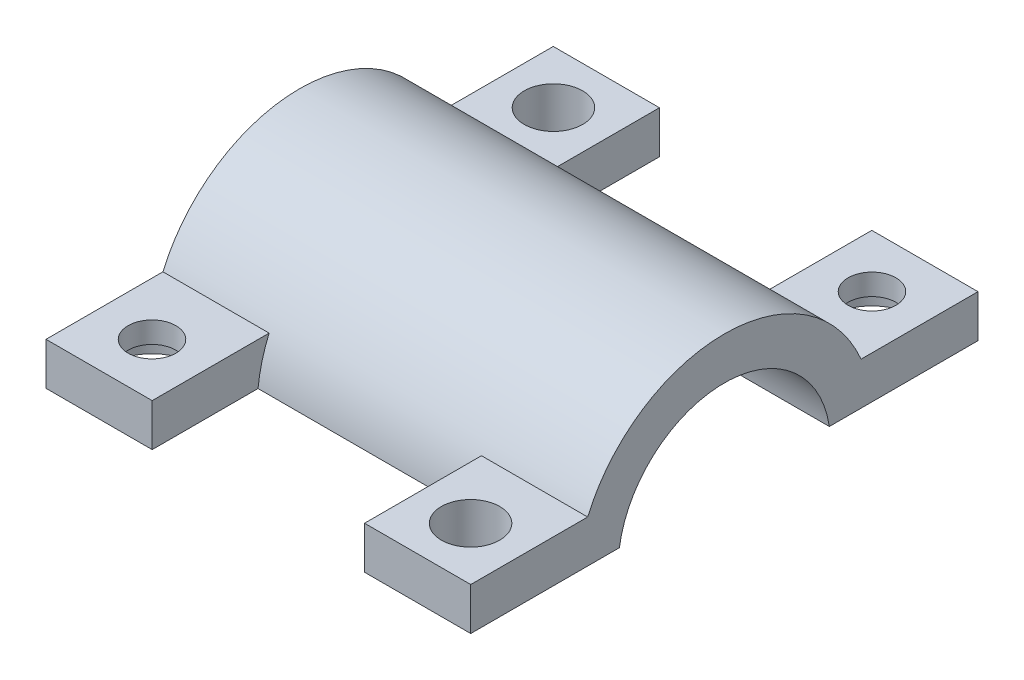
SolidWorks part; units mm, degrees
ref_plane "Front Plane" through (0, 0, 0) normal (0, 0, 1) x (1, 0, 0)
ref_plane "Top Plane" through (0, 0, 0) normal (0, 1, 0) x (1, 0, 0)
ref_plane "Right Plane" through (0, 0, 0) normal (1, 0, 0) x (0, 0, -1)
sketch "Sketch1" plane through (0, 0, 0) normal (1, 0, 0) x (0, 0, -1)
  line L0 (-49.4052, 0) -> (68.181, 0) construction
  line L1 (-13.9194, 1.5) -> (-9.8869, 1.5)
  line L2 (9.8869, 1.5) -> (13.9194, 1.5)
  arc A2 (9.8869, 1.5) -> (-9.8869, 1.5) centre (0, 0) ccw
  arc A3 (-13.9194, 1.5) -> (13.9194, 1.5) centre (0, 0) cw
  dimension "D1" = 1.5
  dimension "D2" = 10
  dimension "D3" = 14
extrude "Boss-Extrude2" add sketch "Sketch1" along normal mid plane 40
sketch "Sketch2" plane through (0, 1.5, 0) normal (0, -1, 0) x (1, 0, 0)
  line L0 (-20, -9.8869) -> (-20, -23.8869)
  line L1 (-20, -23.8869) -> (-10, -23.8869)
  line L2 (-10, -23.8869) -> (-10, -9.8869)
  line L3 (20, -9.8869) -> (-20, -9.8869) construction
  line L4 (-10, -9.8869) -> (-20, -9.8869)
  line L5 (-20, -13.9194) -> (-10, -23.8869) construction
  line L6 (-20, -23.8869) -> (-10, -13.9194) construction
  line L7 (20, -13.9194) -> (-20, -13.9194) construction
  line L8 (0, 20.3263) -> (0, -38.5559) construction
  line L9 (-39.4988, 0) -> (58.103, 0) construction
  line L10 (10, -23.8869) -> (10, -9.8869)
  line L11 (20, -23.8869) -> (10, -23.8869)
  line L12 (20, -9.8869) -> (20, -23.8869)
  line L13 (10, -9.8869) -> (20, -9.8869)
  line L14 (-10, 23.8869) -> (-10, 9.8869)
  line L15 (-20, 23.8869) -> (-10, 23.8869)
  line L16 (-20, 9.8869) -> (-20, 23.8869)
  line L17 (-10, 9.8869) -> (-20, 9.8869)
  line L18 (20, 23.8869) -> (10, 23.8869)
  line L19 (20, 9.8869) -> (20, 23.8869)
  line L20 (10, 9.8869) -> (20, 9.8869)
  line L21 (10, 23.8869) -> (10, 9.8869)
  circle A0 centre (-15, -18.9031) radius 2.75
  circle A3 centre (15, 18.9031) radius 2.75
  circle A4 centre (15, -18.9031) radius 2.25
  circle A5 centre (-15, 18.9031) radius 2.25
  dimension "D3" = 5.5
  dimension "D4" = 4.5
  dimension "D5" = 4.5
  dimension "D1" = 10
  dimension "D2" = 14
extrude "Boss-Extrude3" add sketch "Sketch2" against normal blind 4
sketch "Sketch6" plane through (0, 1.5, 0) normal (0, -1, 0) x (1, 0, 0)
  circle A0 centre (-15, 18.9031) radius 4
  circle A1 centre (15, -18.9031) radius 4
  dimension "D1" = 8
  dimension "D2" = 8
extrude "Cut-Extrude1" cut sketch "Sketch6" against normal blind 2
